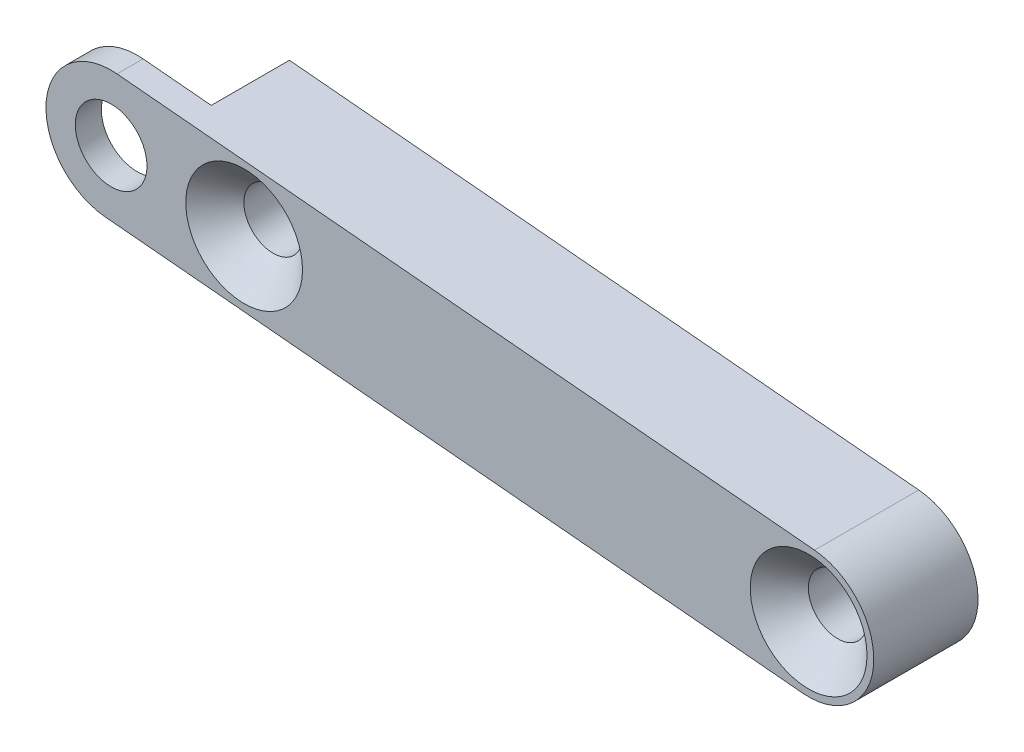
SolidWorks part; units mm, degrees
ref_plane "Front Plane" through (0, 0, 0) normal (0, 0, 1) x (1, 0, 0)
ref_plane "Top Plane" through (0, 0, 0) normal (0, 1, 0) x (1, 0, 0)
ref_plane "Right Plane" through (0, 0, 0) normal (1, 0, 0) x (0, 0, -1)
sketch "Sketch1" plane through (0, 0, 0) normal (0, 0, 1) x (1, 0, 0)
  line L0 (93.3517, 30.1936) -> (50.0319, 34.1486) construction
  line L1 (92.8971, 25.2143) -> (49.5773, 29.1693)
  line L6 (93.8063, 35.1729) -> (50.4865, 39.1279)
  arc A8 (50.9732, 32.7934) -> (49.0906, 35.5038) centre (50.0319, 34.1486) ccw construction
  arc A9 (49.0906, 35.5038) -> (50.9732, 32.7934) centre (50.0319, 34.1486) ccw construction
  arc A10 (94.293, 28.8384) -> (92.4104, 31.5488) centre (93.3517, 30.1936) ccw construction
  arc A11 (92.4104, 31.5488) -> (94.293, 28.8384) centre (93.3517, 30.1936) ccw construction
  arc A12 (50.9732, 32.7934) -> (49.0906, 35.5038) centre (50.0319, 34.1486) ccw construction
  arc A13 (49.0906, 35.5038) -> (50.9732, 32.7934) centre (50.0319, 34.1486) ccw construction
  arc A14 (94.293, 28.8384) -> (92.4104, 31.5488) centre (93.3517, 30.1936) ccw construction
  arc A15 (92.4104, 31.5488) -> (94.293, 28.8384) centre (93.3517, 30.1936) ccw construction
  arc A16 (92.8971, 25.2143) -> (93.8063, 35.1729) centre (93.3517, 30.1936) ccw
  arc A17 (50.4865, 39.1279) -> (49.5773, 29.1693) centre (50.0319, 34.1486) ccw
  point P4 (71.6918, 32.1711)
  dimension "D1" = 5
extrude "Boss-Extrude1" add sketch "Sketch1" along normal blind 8
hole_wizard "CSK for M4 Hex Socket Countersunk Cap Screw1" positions "Sketch4" profile "Sketch5" countersink size "M4" standard "ISO" end condition up to next
sketch "Sketch4" plane through (0, 0, 8) normal (0, 0, 1) x (1, 0, 0)
  arc A0 (94.293, 28.8384) -> (92.4104, 31.5488) centre (93.3517, 30.1936) ccw construction
  arc A1 (92.4104, 31.5488) -> (94.293, 28.8384) centre (93.3517, 30.1936) ccw construction
  arc A2 (49.0906, 35.5038) -> (50.9732, 32.7934) centre (50.0319, 34.1486) ccw construction
  arc A3 (50.9732, 32.7934) -> (49.0906, 35.5038) centre (50.0319, 34.1486) ccw construction
  arc A4 (94.293, 28.8384) -> (92.4104, 31.5488) centre (93.3517, 30.1936) ccw construction
  arc A5 (92.4104, 31.5488) -> (94.293, 28.8384) centre (93.3517, 30.1936) ccw construction
  arc A6 (49.0906, 35.5038) -> (50.9732, 32.7934) centre (50.0319, 34.1486) ccw construction
  arc A7 (50.9732, 32.7934) -> (49.0906, 35.5038) centre (50.0319, 34.1486) ccw construction
  point P1 (93.3517, 30.1936)
  point P7 (50.0319, 34.1486)
sketch "Sketch5" plane through (93.3517, 30.1936, 8) normal (1, 0, 0) x (0, -1, 0)
  line L0 (0, 0) -> (0, 8)
  line L1 (0, 8) -> (2.25, 8)
  line L2 (2.25, 8) -> (2.25, 2.23)
  line L3 (2.25, 2.23) -> (4.48, 0)
  line L5 (4.48, 0) -> (0, 0)
  line L6 (-2.25, 2.23) -> (-4.48, 0) construction
  line L11 (0, -6.35) -> (0, 107.95) construction
  dimension "Thru Hole Dia." = 4.5
  dimension "Thru Hole Depth" = 8
  dimension "Near C'Sink Dia." = 8.96
  dimension "Near C'Sink Angle" = 90
sketch "Sketch6" plane through (0, 0, 8) normal (0, 0, 1) x (1, 0, 0)
  line L0 (39.8243, 35.0805) -> (71.6918, 32.1711) construction
  line L3 (93.8063, 35.1729) -> (50.4865, 39.1279) construction
  line L6 (39.3697, 30.1012) -> (49.5773, 29.1693)
  line L7 (50.4865, 39.1279) -> (40.2789, 40.0598)
  line L10 (93.8063, 35.1729) -> (50.4865, 39.1279)
  line L11 (49.5773, 29.1693) -> (92.8971, 25.2143)
  line L12 (93.8063, 35.1729) -> (50.4865, 39.1279) construction
  line L13 (49.5773, 29.1693) -> (92.8971, 25.2143) construction
  arc A4 (40.2789, 40.0598) -> (39.3697, 30.1012) centre (39.8243, 35.0805) ccw
  arc A5 (57.2872, 52.9093) -> (86.0963, 11.4329) centre (71.6918, 32.1711) ccw
  arc A6 (86.0963, 11.4329) -> (57.2872, 52.9093) centre (71.6918, 32.1711) ccw
  arc A7 (57.2872, 52.9093) -> (86.0963, 11.4329) centre (71.6918, 32.1711) ccw construction
  arc A8 (86.0963, 11.4329) -> (57.2872, 52.9093) centre (71.6918, 32.1711) ccw construction
  arc A9 (39.3697, 30.1012) -> (44.8036, 34.6259) centre (39.8243, 35.0805) ccw construction
  arc A10 (92.8971, 25.2143) -> (93.8063, 35.1729) centre (93.3517, 30.1936) ccw
  arc A11 (50.4865, 39.1279) -> (49.5773, 29.1693) centre (50.0319, 34.1486) ccw
  arc A14 (92.8971, 25.2143) -> (93.8063, 35.1729) centre (93.3517, 30.1936) ccw construction
  arc A15 (50.4865, 39.1279) -> (49.5773, 29.1693) centre (50.0319, 34.1486) ccw
  arc A16 (44.8036, 34.6259) -> (40.2789, 40.0598) centre (39.8243, 35.0805) ccw construction
  dimension "D2" = 0
  dimension "D4" = 10
  dimension "D1" = 0
  dimension "D3" = 32
extrude "Boss-Extrude2" add sketch "Sketch6" against normal up to surface (8 mm away) up to face at (95.6017, 30.1936, 0)
sketch "Sketch8" plane through (0, 0, 0) normal (0, 0, -1) x (-1, 0, 0)
  line L0 (-39.347, 29.8523) -> (-44.5752, 29.3749)
  line L1 (-40.3016, 40.3088) -> (-45.5299, 39.8314)
  line L2 (-45.5299, 39.8314) -> (-44.5752, 29.3749)
  line L3 (-93.8063, 35.1729) -> (-40.2789, 40.0598) construction
  arc A0 (-39.3697, 30.1012) -> (-40.2789, 40.0598) centre (-39.8243, 35.0805) ccw construction
  arc A1 (-39.3697, 30.1012) -> (-40.2789, 40.0598) centre (-39.8243, 35.0805) ccw construction
  arc A2 (-39.347, 29.8523) -> (-40.3016, 40.3088) centre (-39.8243, 35.0805) ccw
  arc A3 (-45.0526, 34.6032) -> (-39.347, 29.8523) centre (-39.8243, 35.0805) ccw construction
  arc A4 (-40.3016, 40.3088) -> (-45.0526, 34.6032) centre (-39.8243, 35.0805) ccw construction
  dimension "D1" = 10.5
extrude "Cut-Extrude1" cut sketch "Sketch8" against normal blind 6
hole_wizard "M5 Clearance Hole1" positions "Sketch9" profile "Sketch10" hole size "M5" standard "ISO" end condition up to next
sketch "Sketch9" plane through (0, 0, 6) normal (0, 0, -1) x (-1, 0, 0)
  arc A0 (-39.3697, 30.1012) -> (-40.2789, 40.0598) centre (-39.8243, 35.0805) ccw construction
  point P0 (-39.8243, 35.0805)
sketch "Sketch10" plane through (39.8243, 35.0805, 6) normal (1, 0, 0) x (0, 1, 0)
  line L0 (0, 0) -> (0, 2)
  line L1 (0, 2) -> (2.75, 2)
  line L2 (2.75, 2) -> (2.75, 0)
  line L5 (2.75, 0) -> (0, 0)
  line L11 (0, -6.35) -> (0, 107.95) construction
  dimension "Thru Hole Dia." = 5.5
  dimension "Thru Hole Depth" = 2
